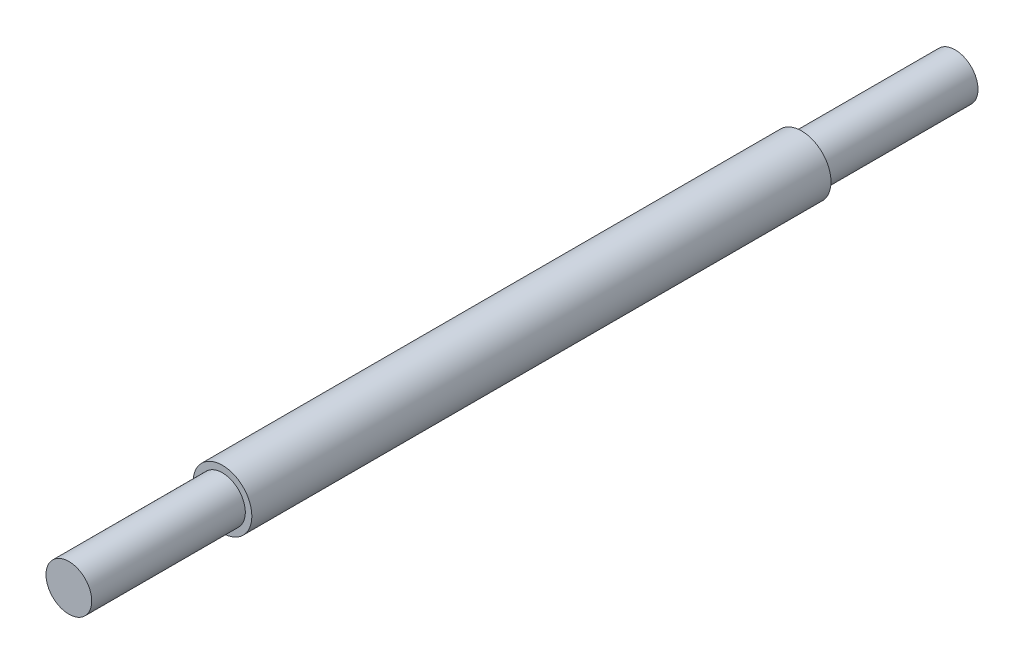
SolidWorks part; units mm, degrees
ref_plane "Front Plane" through (0, 0, 0) normal (0, 0, 1) x (1, 0, 0)
ref_plane "Top Plane" through (0, 0, 0) normal (0, 1, 0) x (1, 0, 0)
ref_plane "Right Plane" through (0, 0, 0) normal (1, 0, 0) x (0, 0, -1)
sketch "Sketch1" plane through (0, 0, 0) normal (0, 0, 1) x (1, 0, 0)
  circle A0 centre (0, 0) radius 3.6
  dimension "D1" = 7.2
extrude "Boss-Extrude1" add sketch "Sketch1" along normal blind 70.9
sketch "Sketch2" plane through (0, 0, 70.9) normal (0, 0, 1) x (1, 0, 0)
  circle A0 centre (0, 0) radius 2.8
  dimension "D1" = 5.6
extrude "Boss-Extrude2" add sketch "Sketch2" along normal blind 18.8
sketch "Sketch3" plane through (0, 0, 0) normal (0, 0, -1) x (-1, 0, 0)
  circle A0 centre (0, 0) radius 2.8
  dimension "D1" = 5.6
extrude "Boss-Extrude3" add sketch "Sketch3" along normal blind 18.8
